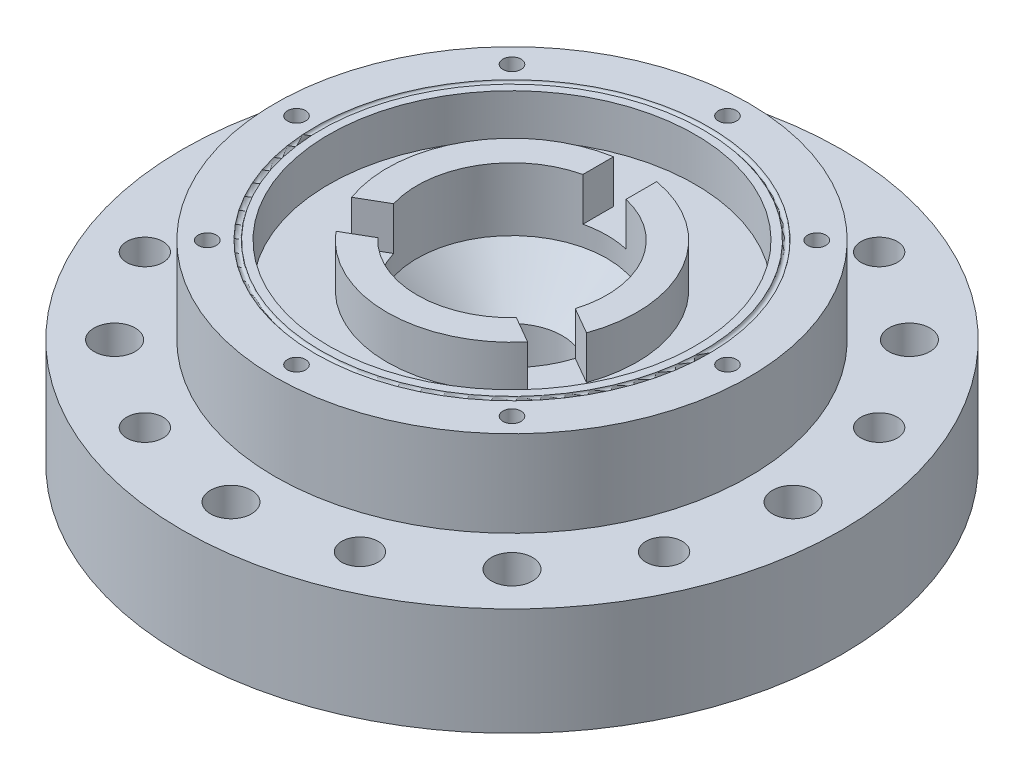
SolidWorks part; units mm, degrees
material "AISI 1020"
ref_plane "Front Plane" through (0, 0, 0) normal (0, 0, 1) x (1, 0, 0)
ref_plane "Top Plane" through (0, 0, 0) normal (0, 1, 0) x (1, 0, 0)
ref_plane "Right Plane" through (0, 0, 0) normal (1, 0, 0) x (0, 0, -1)
sketch "Sketch3" plane through (0, 0, 0) normal (1, 0, 0) x (0, 0, -1)
  line L2 (76.5, 15) -> (55, 15)
  line L3 (55, 15) -> (55, 35)
  line L4 (55, 35) -> (22.025, 35)
  line L7 (11.665, 0) -> (16.665, 0)
  line L8 (76.5, 15) -> (76.5, -10)
  line L9 (53.85, -10) -> (53.85, 86.2223) construction
  line L10 (76.5, -10) -> (53.85, -10)
  line L11 (11.665, 0) -> (11.665, 10)
  line L12 (11.665, 10) -> (22.025, 20.36)
  line L13 (22.025, 20.36) -> (22.025, 35)
  line L14 (0, 0) -> (0, 51.2471) construction
  line L15 (11.665, 10) -> (19.7366, 10) construction
  line L16 (65.2, -29.1535) -> (65.2, 61.9555) construction
  line L17 (0, 0) -> (11.665, 0) construction
  arc A3 (53.85, -10) -> (16.665, 0) centre (30.7197, -21.8739) ccw
  dimension "D6" = 26
  dimension "D1" = 10
  dimension "D2" = 55
  dimension "D3" = 76.5
  dimension "D4" = 45
  dimension "D5" = 53.85
  dimension "D7" = 11.665
  dimension "D9" = 25
  dimension "D11" = 10
  dimension "D12" = 45
  dimension "D13" = 44.05
  dimension "D14" = 5
  dimension "D15" = 65.2
revolve "Revolve1" add sketch "Sketch3" angle 360 about L14
sketch "Sketch4" plane through (0, 0, 0) normal (0, 1, 0) x (1, 0, 0)
  line L0 (0, 0) -> (-65.2, 0) construction
  circle A0 centre (-65.2, 0) radius 4.7625
  dimension "D2" = 9.525
  dimension "D1" = 65.2
extrude "Cut-Extrude2" cut sketch "Sketch4" along normal through all both and the other way through all contours A0
pattern_circular "CirPattern1" count 8 over 360 about axis through (0, 0, 0) along (0, 1, 0) of "Cut-Extrude2"
sketch "Sketch6" plane through (0, 35, 0) normal (0, 1, 0) x (1, 0, 0)
  circle A0 centre (0, 0) radius 29
  circle A1 centre (0, 0) radius 42.5
  point P19 (0, 0)
  dimension "D1" = 58
  dimension "D2" = 85
extrude "Cut-Extrude3" cut sketch "Sketch6" against normal blind 10
sketch "Sketch7" plane through (0, 35, 0) normal (0, 1, 0) x (1, 0, 0)
  line L0 (0, 0) -> (0, 29) construction
  line L1 (-5, 29) -> (5, 29)
  line L2 (5, 29) -> (5, 21.45)
  line L3 (5, 21.45) -> (-5, 21.45)
  line L4 (-5, 21.45) -> (-5, 29)
  circle A0 centre (0, 0) radius 29 construction
  circle A1 centre (0, 0) radius 22.025 construction
  point P8 (0, 29)
  dimension "D1" = 10
extrude "Cut-Extrude4" cut sketch "Sketch7" against normal blind 10
pattern_circular "CirPattern2" count 3 over 360 about axis through (0, 0, 0) along (0, 1, 0) of "Cut-Extrude4"
sketch "Sketch9" plane through (0, 35, 0) normal (0, 1, 0) x (1, 0, 0)
  line L0 (0, 0) -> (46.194, 19.1342) construction
  line L1 (0, 0) -> (100.5921, 0) construction
  circle A0 centre (46.194, 19.1342) radius 2
  dimension "D2" = 4
  dimension "D1" = 50
  dimension "D3" = 22.5
sketch "Sketch10" plane through (0, 35, 0) normal (0, 1, 0) x (1, 0, 0)
  circle A2 centre (0, 0) radius 45
  dimension "D1" = 90
sketch "Sketch11" plane through (0, 15, 0) normal (0, 1, 0) x (1, 0, 0)
  line L0 (-46.1034, 46.1034) -> (-65.2, 0) construction
  line L1 (0, 0) -> (-88.6644, 36.726) construction
  circle A0 centre (0, 0) radius 65.2 construction
  dimension "D1" = 130.4
hole_wizard "Tap Drill for 3/8-24 Tap1" positions "Sketch14" profile "Sketch15" hole size "3/8-24" standard "ANSI Inch"
sketch "Sketch14" plane through (0, 15, 0) normal (0, 1, 0) x (1, 0, 0)
  line L0 (0, 0) -> (-88.6644, 36.726) construction
  circle A0 centre (0, 0) radius 65.2 construction
  point P0 (-60.2369, 24.951)
  dimension "D1" = 65.2
sketch "Sketch15" plane through (-60.2369, 15, -24.951) normal (1, 0, 0) x (0, 0, 1)
  line L0 (0, 0) -> (0, 27.5335)
  line L1 (0, 27.5335) -> (4.2164, 25)
  line L2 (4.2164, 25) -> (4.2164, 0)
  line L5 (4.2164, 0) -> (0, 0)
  line L10 (0, 27.5335) -> (-4.2164, 25) construction
  line L11 (0, -6.35) -> (0, 107.95) construction
  dimension "Hole Dia." = 8.4328
  dimension "Hole Depth" = 25
  dimension "Drill Angle" = 118
cosmetic thread "Cosmetic Thread17" parameters "D2"=9.525
pattern_circular "CirPattern4" count 8 over 360 about axis through (0, 0, 0) along (0, 1, 0) of "Tap Drill for 3/8-24 Tap1"
cosmetic thread "Cosmetic Thread18" parameters "D2"=9.525
cosmetic thread "Cosmetic Thread19" parameters "D2"=9.525
cosmetic thread "Cosmetic Thread20" parameters "D2"=9.525
cosmetic thread "Cosmetic Thread21" parameters "D2"=9.525
cosmetic thread "Cosmetic Thread22" parameters "D2"=9.525
cosmetic thread "Cosmetic Thread23" parameters "D2"=9.525
cosmetic thread "Cosmetic Thread24" parameters "D2"=9.525
sketch "Sketch16" plane through (0, 35, 0) normal (0, 1, 0) x (1, 0, 0)
  circle A0 centre (0, 0) radius 50 construction
  dimension "D1" = 100
hole_wizard "Tap Drill for M5x0.8 Tap1" positions "Sketch24" profile "Sketch20" hole size "M5x0.8" standard "ANSI Metric"
sketch "Sketch24" plane through (0, 35, 0) normal (0, 1, 0) x (1, 0, 0)
  circle A0 centre (0, 0) radius 50 construction
  point P0 (-50, 0)
sketch "Sketch20" plane through (-50, 35, 0) normal (1, 0, 0) x (0, 0, 1)
  line L0 (0, 0) -> (0, 21.2618)
  line L1 (0, 21.2618) -> (2.1, 20)
  line L2 (2.1, 20) -> (2.1, 0)
  line L5 (2.1, 0) -> (0, 0)
  line L10 (0, 21.2618) -> (-2.1, 20) construction
  line L11 (0, -6.35) -> (0, 107.95) construction
  dimension "Hole Dia." = 4.2
  dimension "Hole Depth" = 20
  dimension "Drill Angle" = 118
cosmetic thread "Cosmetic Thread25" parameters "D2"=5.4864
pattern_circular "CirPattern5" count 8 over 360 about axis through (0, 0, 0) along (0, 1, 0) of "Tap Drill for M5x0.8 Tap1"
cosmetic thread "Cosmetic Thread26" parameters "D2"=5.4864
cosmetic thread "Cosmetic Thread27" parameters "D2"=5.4864
cosmetic thread "Cosmetic Thread28" parameters "D2"=5.4864
cosmetic thread "Cosmetic Thread29" parameters "D2"=5.4864
cosmetic thread "Cosmetic Thread30" parameters "D2"=5.4864
cosmetic thread "Cosmetic Thread31" parameters "D2"=5.4864
cosmetic thread "Cosmetic Thread32" parameters "D2"=5.4864
sketch "Sketch25" plane through (0, -10, 0) normal (0, -1, 0) x (1, 0, 0)
  circle A0 centre (0, 0) radius 53.85
  circle A1 centre (0, 0) radius 56.85
  dimension "D1" = 3
extrude "Boss-Extrude1" add sketch "Sketch25" along normal blind 6
fillet "Fillet1" radius 10 1 edges at (0, -10, -53.85)
sketch "Sketch26" plane through (0, -10, 0) normal (0, -1, 0) x (1, 0, 0)
  circle A0 centre (0, 0) radius 58
  dimension "D1" = 116
sweep "Cut-Sweep1" cut path "Sketch26" circular profile diameter 1.25 parameters "D3"=1.25
sweep "Cut-Sweep2" cut path "Sketch10" circular profile diameter 1.25 parameters "D3"=1.25
